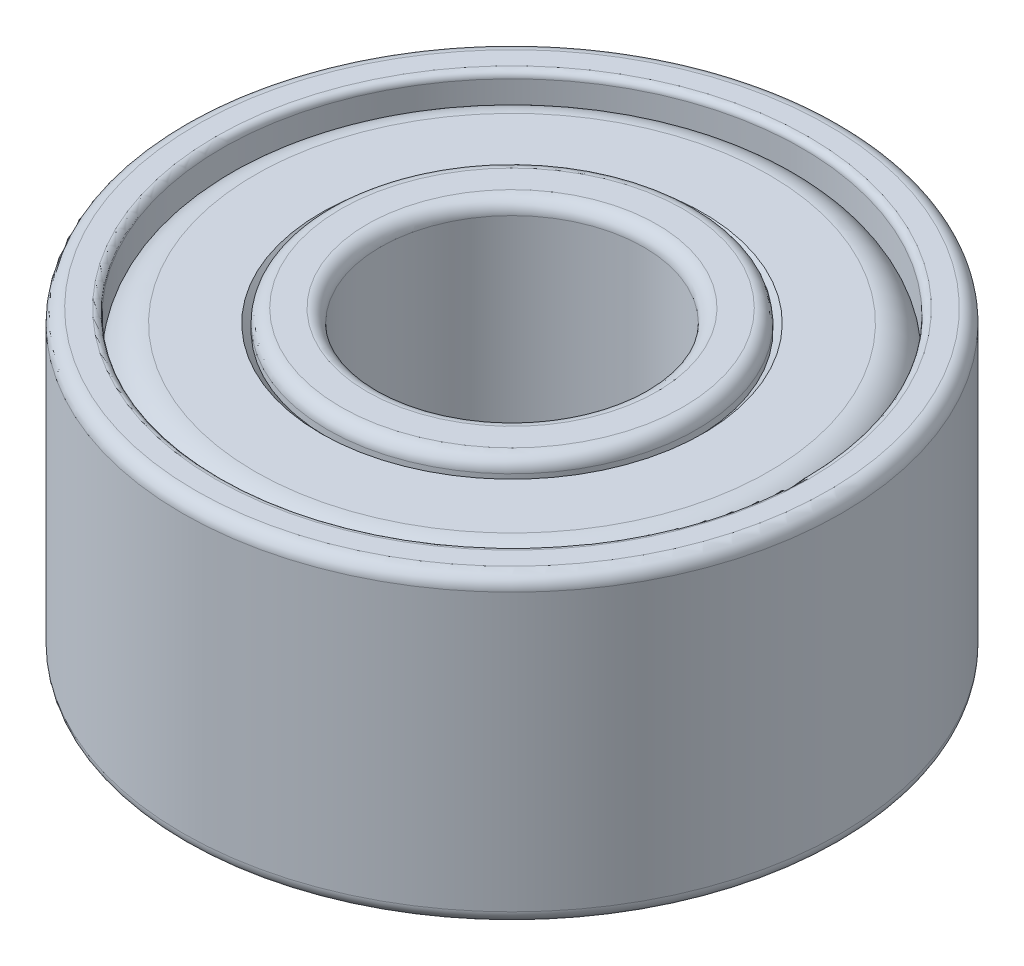
SolidWorks part; units mm, degrees
material "1060 Alloy"
ref_plane "Front Plane" through (0, 0, 0) normal (0, 0, 1) x (1, 0, 0)
ref_plane "Top Plane" through (0, 0, 0) normal (0, 1, 0) x (1, 0, 0)
ref_plane "Right Plane" through (0, 0, 0) normal (1, 0, 0) x (0, 0, -1)
sketch "Sketch2" plane through (0, 0, 0) normal (0, 1, 0) x (1, 0, 0)
  circle A0 centre (0, 0) radius 1
  circle A1 centre (0, 0) radius 1.4
  dimension "D1" = 2
  dimension "D2" = 0.4
extrude "Boss-Extrude1" add sketch "Sketch2" along normal mid plane 2.3
sketch "Sketch4" plane through (0, 0, 0) normal (0, 1, 0) x (1, 0, 0)
  circle A0 centre (0, 0) radius 2.5
  circle A1 centre (0, 0) radius 2.2
  dimension "D1" = 5
  dimension "D2" = 0.3
extrude "Boss-Extrude2" add sketch "Sketch4" along normal mid plane 2.3 separate body
fillet "Fillet1" radius 0.1 4 edges at (0, -1.15, 1) (0, -1.15, 1.4) (0, 1.15, 1) (0, 1.15, 1.4)
fillet "Fillet2" radius 0.1 2 edges at (0, -1.15, 2.5) (0, 1.15, 2.5)
fillet "Fillet3" radius 0.05 2 edges at (0, -1.15, 2.2) (0, 1.15, 2.2)
sketch "Sketch5" plane through (0, 0, 0) normal (0, 1, 0) x (1, 0, 0)
  circle A0 centre (0, 0) radius 2.2
  circle A1 centre (0, 0) radius 2.2 construction
  circle A2 centre (0, 0) radius 1.4
  circle A3 centre (0, 0) radius 1.4 construction
extrude "Boss-Extrude3" add sketch "Sketch5" along normal mid plane 2.1 separate body
fillet "Fillet4" radius 0.25 2 edges at (0, -1.05, 2.2) (0, 1.05, 2.2)
chamfer "Chamfer1" distance 0.05 angle 45 2 edges at (0, -1.05, 1.4) (0, 1.05, 1.4)
